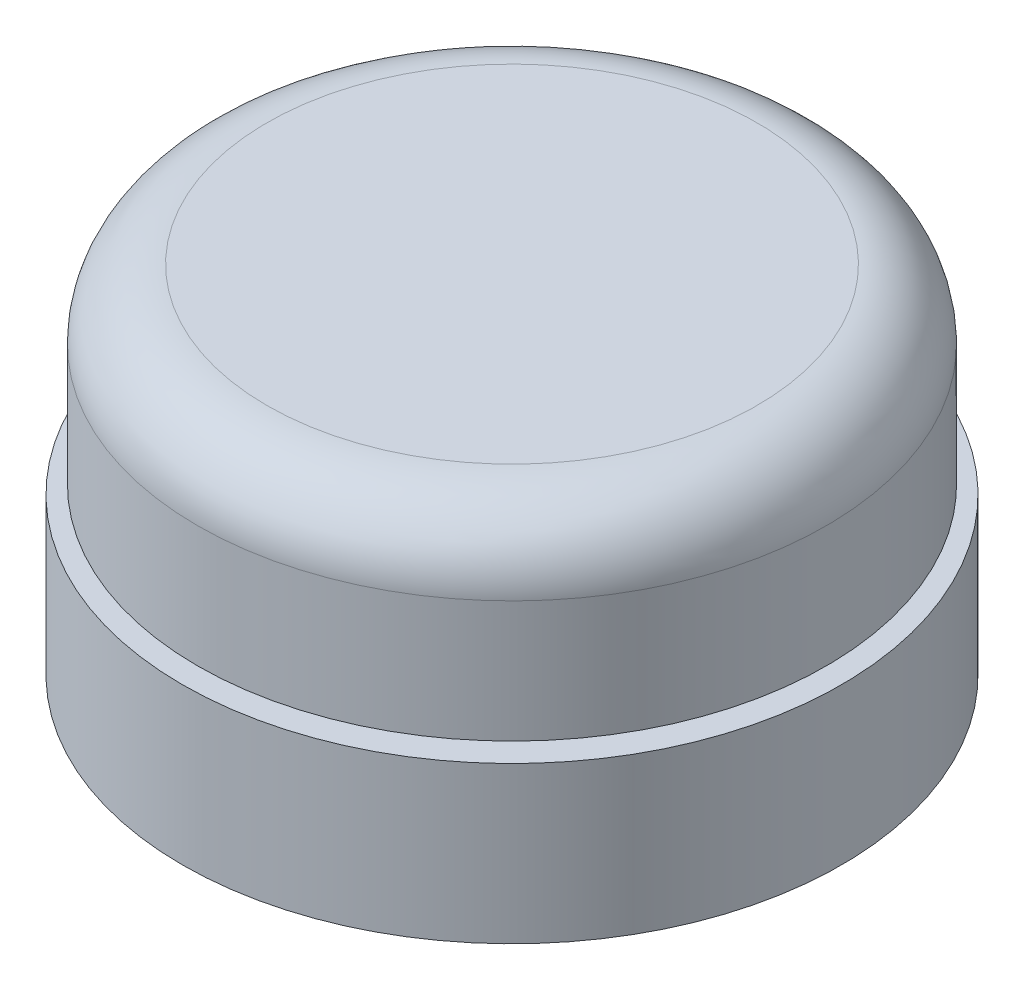
SolidWorks part; units mm, degrees
ref_plane "前视基准面" through (0, 0, 0) normal (0, 0, 1) x (1, 0, 0)
ref_plane "上视基准面" through (0, 0, 0) normal (0, 1, 0) x (1, 0, 0)
ref_plane "右视基准面" through (0, 0, 0) normal (1, 0, 0) x (0, 0, -1)
sketch "草图1" plane through (0, 0, 0) normal (0, 1, 0) x (1, 0, 0)
  circle A0 centre (0, 0) radius 38
  dimension "D1" = 76
extrude "凸台-拉伸1" add sketch "草图1" along normal blind 18
sketch "草图2" plane through (0, 18, 0) normal (0, 1, 0) x (1, 0, 0)
  circle A0 centre (0, 0) radius 28.6727
extrude "凸台-拉伸2" add sketch "草图2" along normal blind 1
sketch "草图3" plane through (0, 19, 0) normal (0, 1, 0) x (1, 0, 0)
  circle A0 centre (0, 0) radius 36.25
  dimension "D1" = 72.5
extrude "凸台-拉伸3" add sketch "草图3" along normal blind 22
fillet "圆角1" radius 8 1 edges at (0, 41, 36.25)
sketch "草图4" plane through (0, 0, 0) normal (0, -1, 0) x (1, 0, 0)
  line L0 (-38, 0) -> (38, 0) construction
  circle A0 centre (0, 0) radius 38 construction
  circle A1 centre (-29.5, 0) radius 1.5
  circle A2 centre (-20.8597, 20.8597) radius 1.5
  circle A3 centre (0, 29.5) radius 1.5
  circle A4 centre (20.8597, 20.8597) radius 1.5
  circle A5 centre (-34.5, 0) radius 1.5
  circle A6 centre (29.5, 0) radius 1.5
  circle A7 centre (20.8597, -20.8597) radius 1.5
  circle A8 centre (0, -29.5) radius 1.5
  circle A9 centre (-20.8597, -20.8597) radius 1.5
  point P17 (0, 0)
  dimension "D1" = 3
  dimension "D4" = 3
  dimension "D2" = 29.5
  dimension "D5" = 5
  dimension "D3" = 8
extrude "切除-拉伸1" cut sketch "草图4" against normal blind 5
sketch "草图5" plane through (0, 0, 0) normal (1, 0, 0) x (0, 0, -1)
  line L0 (0, 40.9799) -> (0, 0) construction
  line L1 (-36.25, 33) -> (36.25, 33) construction
  line L2 (24, 31) -> (-24, 31)
  line L3 (24, 31) -> (24, 21)
  line L4 (24, 21) -> (-24, 21)
  line L5 (-24, 31) -> (-24, 21)
  dimension "D1" = 10
  dimension "D2" = 48
  dimension "D3" = 24
  dimension "D4" = 2
extrude "切除-拉伸2" cut sketch "草图5" against normal blind 100 from offset 20
